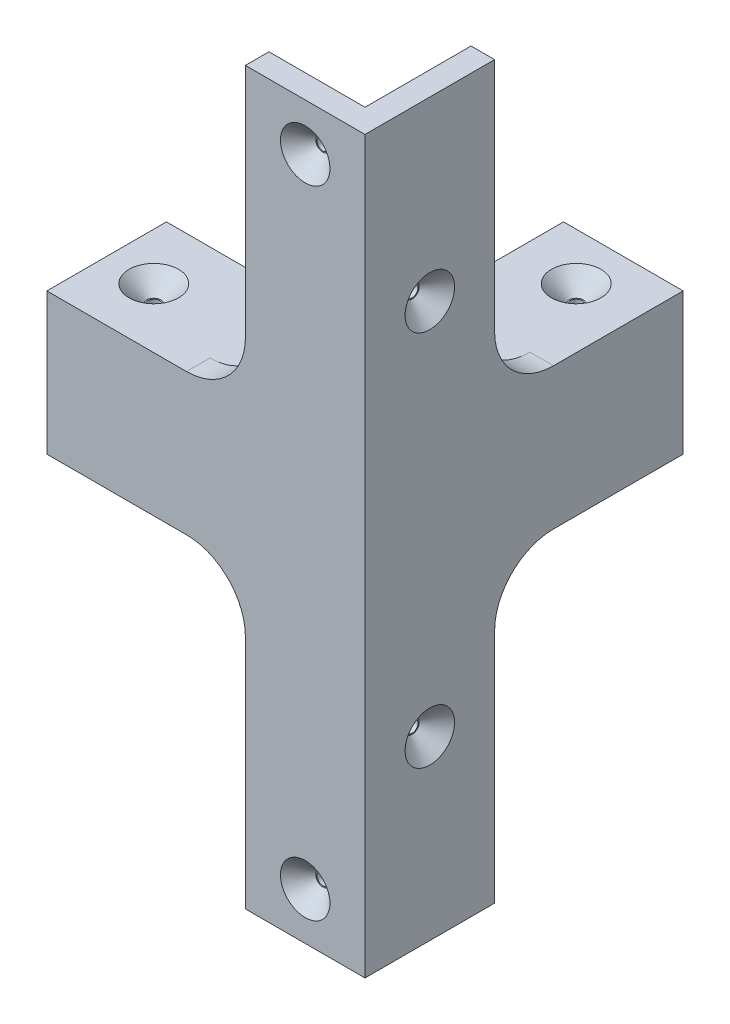
SolidWorks part; units mm, degrees
ref_plane "Front Plane" through (0, 0, 0) normal (0, 0, 1) x (1, 0, 0)
ref_plane "Top Plane" through (0, 0, 0) normal (0, 1, 0) x (1, 0, 0)
ref_plane "Right Plane" through (0, 0, 0) normal (1, 0, 0) x (0, 0, -1)
sketch "Sketch1" plane through (0, 0, 0) normal (0, 1, 0) x (1, 0, 0)
  line L1 (0, 0) -> (-54, 0)
  line L2 (0, 0) -> (0, 20.3)
  line L3 (0, 20.3) -> (-54, 20.3)
  line L4 (-54, 0) -> (-54, 20.3)
  line L5 (0, 0) -> (-20.3, 0)
  line L6 (0, 0) -> (0, 54)
  line L7 (0, 54) -> (-20.3, 54)
  line L8 (-20.3, 0) -> (-20.3, 54)
  point P8 (-20.3, 35.9378)
  dimension "D1" = 20.3
  dimension "D2" = 20.3
  dimension "D3" = 54
  dimension "D4" = 54
extrude "Boss-Extrude1" add sketch "Sketch1" against normal blind 24 contours L1 L8 L3 L4 | L8 L1 L2 L3 | L8 L3 L6 L7
shell "Shell1" thickness 4
sketch "Sketch2" plane through (0, 0, 0) normal (0, 1, 0) x (1, 0, 0)
  line L0 (-54, 10.15) -> (0, 10.15) construction
  line L1 (-54, 0) -> (-54, 20.3) construction
  line L2 (0, 0) -> (0, 54) construction
  line L3 (0, 10.15) -> (0, 54) construction
  line L4 (0, 54) -> (-10.15, 54) construction
  line L5 (0, 54) -> (-20.3, 54) construction
  line L6 (-10.15, 54) -> (-10.15, 0) construction
  line L7 (0, 0) -> (-54, 0) construction
  circle A0 centre (-10.15, 46) radius 1
  circle A1 centre (-46, 10.15) radius 1
  dimension "D1" = 2
  dimension "D2" = 2
  dimension "D3" = 8
  dimension "D4" = 8
extrude "Cut-Extrude1" cut sketch "Sketch2" against normal blind 24
sketch "Sketch3" plane through (0, 0, 0) normal (0, 1, 0) x (1, 0, 0)
  circle A0 centre (-46, 10.15) radius 4.2
  circle A1 centre (-10.15, 46) radius 4.2
  dimension "D1" = 8.4
  dimension "D2" = 8.4
extrude "Cut-Extrude2" cut sketch "Sketch3" against normal blind 3 draft 45
sketch "Sketch4" plane through (0, 0, 0) normal (0, 1, 0) x (1, 0, 0)
  line L1 (0, 0) -> (-20.3, 0)
  line L2 (0, 0) -> (0, 22)
  line L3 (0, 22) -> (-20.3, 22)
  line L4 (-20.3, 0) -> (-20.3, 22)
  line L5 (-20.3, 20.3) -> (-20.3, 54) construction
  point P5 (-20.3, 11)
  dimension "D1" = 22
extrude "Boss-Extrude2" add sketch "Sketch4" along normal blind 50 separate body
shell "Shell2" thickness 4
combine bodies "Combine1" operation type add bodies to combine 103 104
sketch "Sketch5" plane through (0, 0, 0) normal (0, 0, 1) x (1, 0, 0)
  line L0 (-20.3, 50) -> (0, 50) construction
  circle A0 centre (-10.15, 42) radius 1
  point P4 (-10.15, 50)
  dimension "D1" = 2
  dimension "D2" = 8
extrude "Cut-Extrude3" cut sketch "Sketch5" against normal up to next
sketch "Sketch6" plane through (0, 0, 0) normal (0, 0, 1) x (1, 0, 0)
  circle A0 centre (-10.15, 42) radius 4.2
  dimension "D1" = 8.4
extrude "Cut-Extrude4" cut sketch "Sketch6" against normal blind 3 draft 45
ref_plane "Plane1" through (0, 0, 0) normal (-0.7071, 0, 0.7071) x (0.7071, 0, 0.7071)
sketch "Sketch7" plane through (0, 0, 0) normal (1, 0, 0) x (0, 0, -1)
  line L0 (0, 50) -> (22, 50) construction
  circle A0 centre (11, 20) radius 1
  point P4 (11, 50)
  dimension "D1" = 2
  dimension "D2" = 30
extrude "Cut-Extrude5" cut sketch "Sketch7" against normal up to next
sketch "Sketch8" plane through (0, 0, 0) normal (1, 0, 0) x (0, 0, -1)
  circle A0 centre (11, 20) radius 4.2
  dimension "D1" = 8.4
extrude "Cut-Extrude6" cut sketch "Sketch8" against normal blind 3 draft 45
fillet "Fillet1" radius 10 2 edges at (-20.3, 0, -2) (-2, 0, -22)
ref_plane "Plane2" through (0, -12, 0) normal (0, -1, 0) x (-1, 0, 0)
sketch "Sketch9" plane through (0, -24, 0) normal (0, -1, 0) x (1, 0, 0)
  line L6 (-4, -4) -> (-4, -22)
  line L7 (-20.3, -4) -> (-4, -4)
  line L8 (-20.3, 0) -> (-20.3, -4)
  line L9 (0, 0) -> (-20.3, 0)
  line L10 (0, -22) -> (0, 0)
  line L11 (-4, -22) -> (0, -22)
  line L12 (-4, -4) -> (-4, -22)
  line L13 (-20.3, -4) -> (-4, -4)
  line L14 (-20.3, 0) -> (-20.3, -4)
  line L15 (0, 0) -> (-20.3, 0)
  line L16 (0, -22) -> (0, 0)
  line L17 (-4, -22) -> (0, -22)
  dimension "D1" = 0
extrude "Boss-Extrude3" add sketch "Sketch9" along normal blind 50
mirror "Mirror4" about plane through (0, -12, 0) normal (0, -1, 0) of "Cut-Extrude6", "Cut-Extrude5", "Cut-Extrude4", "Cut-Extrude3"
fillet "Fillet2" radius 10 2 edges at (-2, -24, -22) (-20.3, -24, -2)
equation "\"D2@Sketch1\"=\"D1@Sketch1\""
equation "\"D4@Sketch1\"=\"D3@Sketch1\""
equation "\"D2@Sketch2\"=\"D1@Sketch2\""
equation "\"D2@Sketch3\"=\"D1@Sketch3\""
